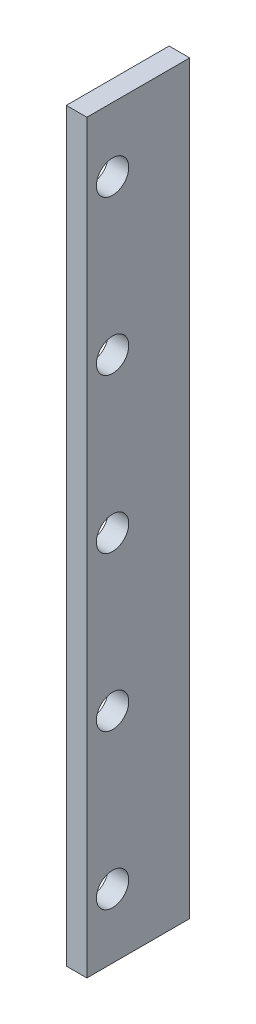
SolidWorks part; units mm, degrees
ref_plane "Front Plane" through (0, 0, 0) normal (0, 0, 1) x (1, 0, 0)
ref_plane "Top Plane" through (0, 0, 0) normal (0, 1, 0) x (1, 0, 0)
ref_plane "Right Plane" through (0, 0, 0) normal (1, 0, 0) x (0, 0, -1)
sketch "Sketch1" plane through (0, 0, 0) normal (0, 1, 0) x (1, 0, 0)
  line L0 (0, 0) -> (16, 0)
  line L1 (16, 0) -> (16, 80)
  line L2 (16, 80) -> (0, 80)
  line L3 (0, 80) -> (0, 0)
  dimension "D1" = 16
  dimension "D2" = 80
extrude "Boss-Extrude1" add sketch "Sketch1" along normal blind 580
sketch "Sketch2" plane through (0, 0, 0) normal (-1, 0, 0) x (0, 0, 1)
  circle A0 centre (-20, 50) radius 12.6
  circle A1 centre (-20, 170) radius 12.6
  circle A2 centre (-20, 290) radius 12.6
  circle A3 centre (-20, 410) radius 12.6
  circle A4 centre (-20, 530) radius 12.6
  dimension "D3" = 25.2
extrude "Cut-Extrude1" cut sketch "Sketch2" against normal through all
